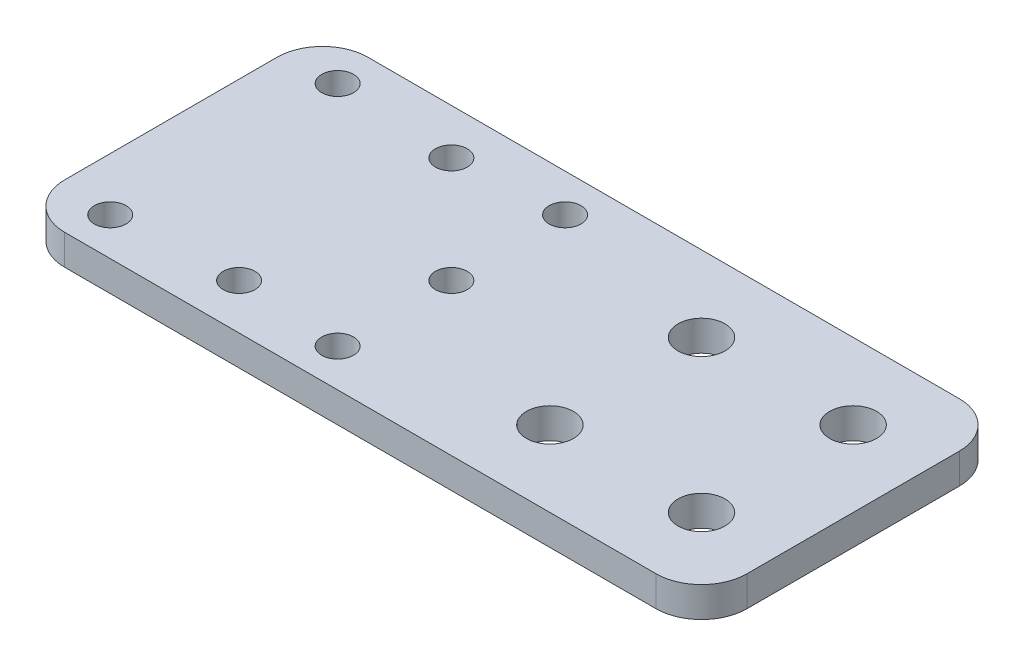
SolidWorks part; units mm, degrees
ref_plane "前视基准面" through (0, 0, 0) normal (0, 0, 1) x (1, 0, 0)
ref_plane "上视基准面" through (0, 0, 0) normal (0, 1, 0) x (1, 0, 0)
ref_plane "右视基准面" through (0, 0, 0) normal (1, 0, 0) x (0, 0, -1)
sketch "草图1" plane through (0, 0, 0) normal (0, 1, 0) x (1, 0, 0)
  line L0 (45, 10) -> (35, 10) construction
  line L1 (0, 0) -> (45, 0)
  line L2 (0, 0) -> (0, 20)
  line L3 (0, 20) -> (45, 20)
  line L4 (45, 0) -> (45, 20)
  line L5 (22, 20) -> (22, 0) construction
  line L6 (30, 5) -> (40, 5) construction
  line L7 (30, 5) -> (30, 15) construction
  line L8 (30, 15) -> (40, 15) construction
  line L9 (40, 5) -> (40, 15) construction
  line L10 (30, 5) -> (40, 15) construction
  line L11 (30, 15) -> (40, 5) construction
  line L12 (22, 10) -> (18.5, 10) construction
  line L13 (11.5, 10) -> (18.5, 10) construction
  line L15 (3.5, 2.5) -> (18.5, 2.5) construction
  line L16 (3.5, 2.5) -> (3.5, 17.5) construction
  line L17 (3.5, 17.5) -> (18.5, 17.5) construction
  line L18 (18.5, 2.5) -> (18.5, 17.5) construction
  line L19 (3.5, 2.5) -> (18.5, 17.5) construction
  line L20 (3.5, 17.5) -> (18.5, 2.5) construction
  circle A0 centre (30, 15) radius 1.55
  circle A1 centre (40, 15) radius 1.55
  circle A2 centre (40, 5) radius 1.55
  circle A3 centre (30, 5) radius 1.55
  circle A4 centre (11.5, 10) radius 7 construction
  circle A5 centre (11.5, 17) radius 1.05
  circle A6 centre (18.5, 10) radius 1.05
  circle A7 centre (11.5, 3) radius 1.05
  circle A8 centre (3.5, 17.5) radius 1.05
  circle A9 centre (18.5, 17.5) radius 1.05
  circle A10 centre (18.5, 2.5) radius 1.05
  circle A11 centre (3.5, 2.5) radius 1.05
  point P26 (11, 10)
  dimension "D5" = 3.1
  dimension "D7" = 14
  dimension "D9" = 2.1
  dimension "D1" = 45
  dimension "D2" = 20
  dimension "D3" = 10
  dimension "D4" = 10
  dimension "D6" = 23
  dimension "D8" = 3.5
  dimension "D10" = 15
extrude "凸台-拉伸1" add sketch "草图1" along normal blind 2
fillet "圆角1" radius 3 4 edges at (0, 1, -20) (45, 1, -20) (45, 1, 0) (0, 1, 0)
